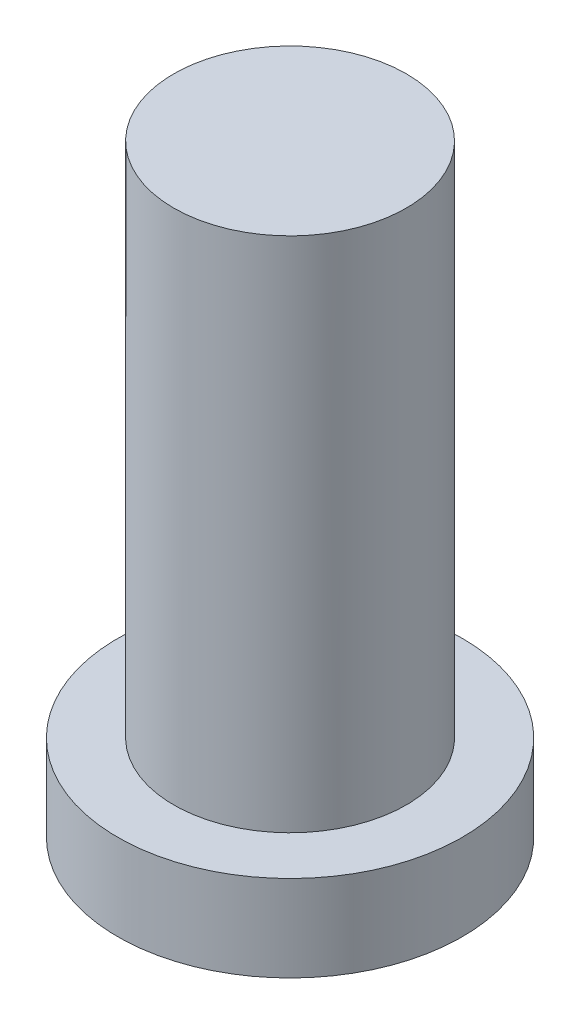
SolidWorks part; units mm, degrees
ref_plane "Front Plane" through (0, 0, 0) normal (0, 0, 1) x (1, 0, 0)
ref_plane "Top Plane" through (0, 0, 0) normal (0, 1, 0) x (1, 0, 0)
ref_plane "Right Plane" through (0, 0, 0) normal (1, 0, 0) x (0, 0, -1)
sketch "Sketch2" plane through (0, 0, 0) normal (0, 1, 0) x (1, 0, 0)
  circle A0 centre (0, 0) radius 1.35
  dimension "D1" = 2.7
extrude "Boss-Extrude1" add sketch "Sketch2" along normal blind 6
sketch "Sketch3" plane through (0, 0, 0) normal (0, -1, 0) x (1, 0, 0)
  circle A0 centre (0, 0) radius 2
extrude "Boss-Extrude2" add sketch "Sketch3" along normal blind 1
